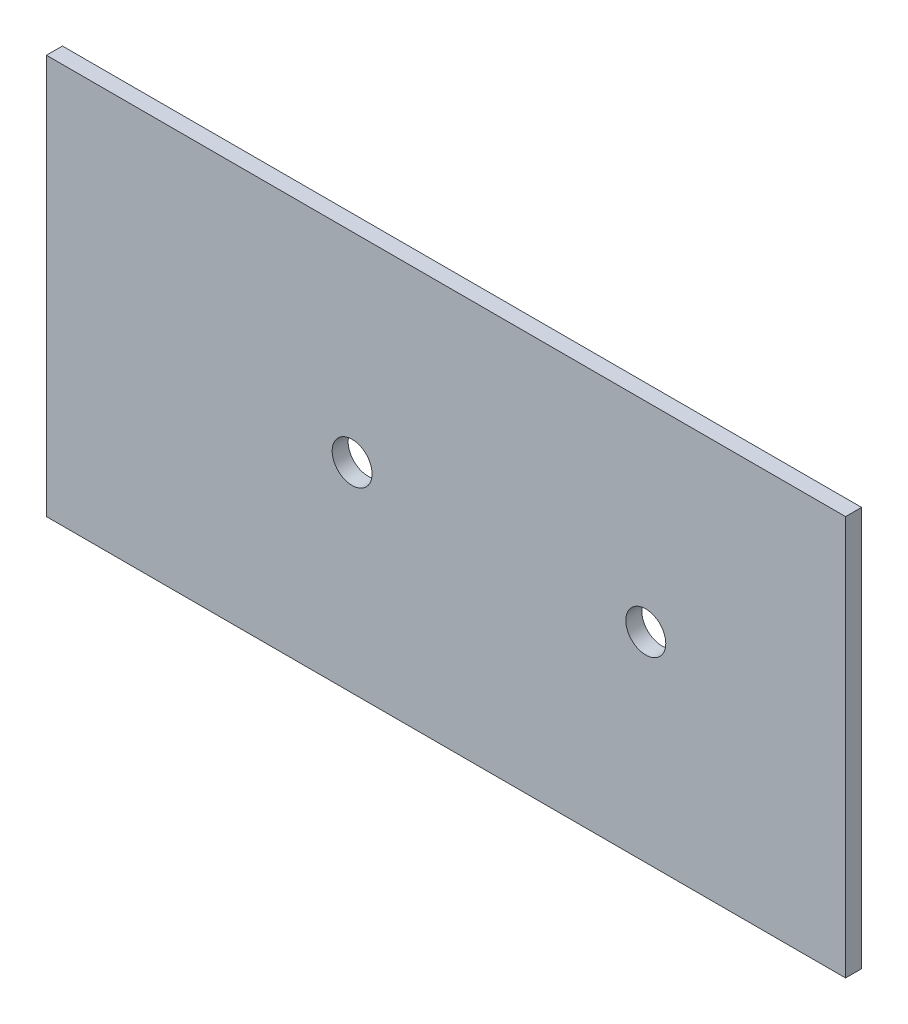
SolidWorks part; units mm, degrees
ref_plane "Front Plane" through (0, 0, 0) normal (0, 0, 1) x (1, 0, 0)
ref_plane "Top Plane" through (0, 0, 0) normal (0, 1, 0) x (1, 0, 0)
ref_plane "Right Plane" through (0, 0, 0) normal (1, 0, 0) x (0, 0, -1)
sketch "Sketch1" plane through (0, 0, 0) normal (0, 0, 1) x (1, 0, 0)
  line L1 (-150, -50) -> (50, -50)
  line L2 (-150, -50) -> (-150, 50)
  line L3 (-150, 50) -> (50, 50)
  line L4 (50, -50) -> (50, 50)
  circle A0 centre (0, 0) radius 5
  circle A2 centre (-73.5, 0) radius 5
  point P1 (0, 0)
  point P9 (0, 0)
  dimension "D3" = 10
  dimension "D4" = 0
  dimension "D1" = 150
  dimension "D2" = 100
  dimension "D8" = 73.5
  dimension "D9" = 50
extrude "Boss-Extrude1" add sketch "Sketch1" along normal blind 4
